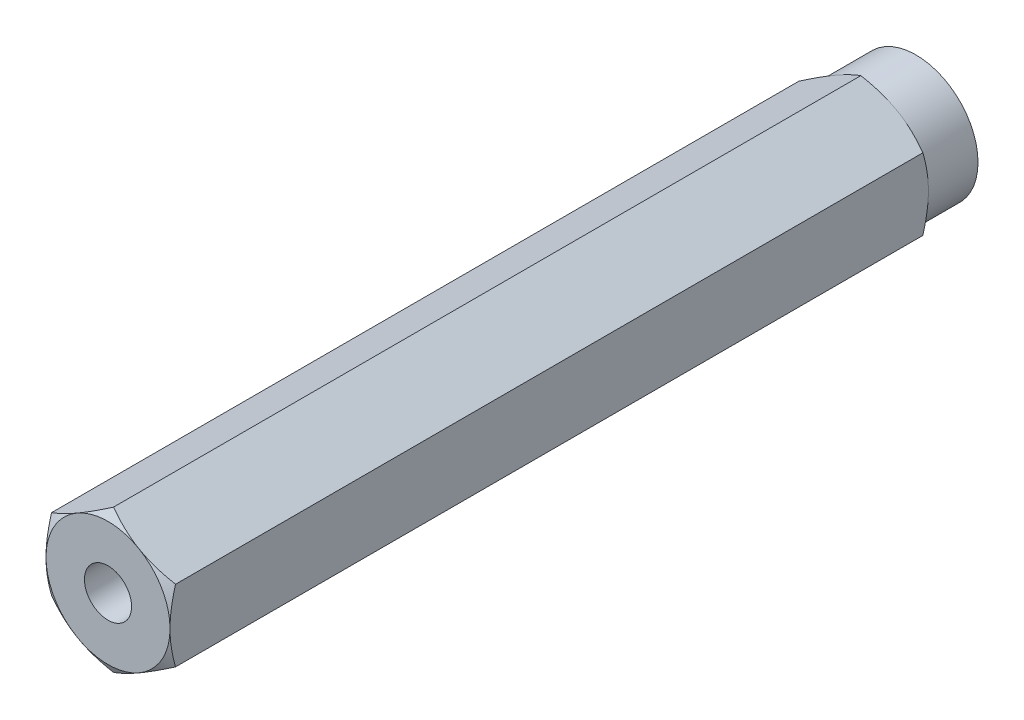
SolidWorks part; units mm, degrees
ref_plane "Front Plane" through (0, 0, 0) normal (0, 0, 1) x (1, 0, 0)
ref_plane "Top Plane" through (0, 0, 0) normal (0, 1, 0) x (1, 0, 0)
ref_plane "Right Plane" through (0, 0, 0) normal (1, 0, 0) x (0, 0, -1)
sketch "Sketch3" plane through (0, 0, 0) normal (1, 0, 0) x (0, 0, -1)
  line L0 (-46.0851, 0) -> (46.0851, 0) construction
  line L1 (0, 6.35) -> (0, -6.35) construction
  line L2 (-46.0851, 2.413) -> (-46.0851, -2.413) construction
  point P2 (33.3851, 0)
  point P3 (-33.3851, 0)
  dimension "Length" = 92.1702
  dimension "Min Thread Length" = 12.7
  dimension "D1" = 12.7
  dimension "Thread Dia" = 4.826
  dimension "Hex" = 12.7
sketch "Sketch1" plane through (0, 0, 0) normal (0, 0, 1) x (1, 0, 0)
  line L1 (0, 7.3323) -> (-6.35, 3.6662)
  line L2 (-6.35, 3.6662) -> (-6.35, -3.6662)
  line L3 (-6.35, -3.6662) -> (0, -7.3323)
  line L4 (0, -7.3323) -> (6.35, -3.6662)
  line L5 (6.35, -3.6662) -> (6.35, 3.6662)
  line L6 (6.35, 3.6662) -> (0, 7.3323)
  circle A0 centre (0, 0) radius 6.35 construction
  circle A1 centre (0, 0) radius 2.413
extrude "Extrude1" add sketch "Sketch1" along normal blind 77.6605
sketch "Sketch11" plane through (0, 0, 0) normal (0, 0, -1) x (-1, 0, 0)
  circle A0 centre (0, 0) radius 2.413 construction
  circle A1 centre (0, 0) radius 2.413
curve "Helix/Spiral1" pitch 0.7937 height 92.964 turns 117.12 parameters "Pitch"=0.7937
sketch "Sketch12" plane through (0, 0, 0) normal (1, 0, 0) x (0, 0, -1)
  line L0 (0.6945, 2.413) -> (0, 2.413)
  line L1 (0.6945, 2.413) -> (0.3969, 1.8974)
  line L2 (0.3969, 1.8974) -> (0.2977, 1.8974)
  line L3 (0.2977, 1.8974) -> (0, 2.413)
  line L4 (0.3473, 1.8974) -> (0.3473, 2.413) construction
  line L5 (0.5457, 2.1552) -> (0.1488, 2.1552) construction
  dimension "D1" = 0.0992
  dimension "D2" = 0.3969
  dimension "D3" = 60
sketch "Sketch6" plane through (0, 0, 0) normal (0, 0, -1) x (-1, 0, 0)
  line L6 (0, 7.3323) -> (-6.35, 3.6662)
  line L7 (-6.35, 3.6662) -> (-6.35, -3.6662)
  line L8 (-6.35, -3.6662) -> (0, -7.3323)
  line L9 (0, -7.3323) -> (6.35, -3.6662)
  line L10 (6.35, -3.6662) -> (6.35, 3.6662)
  line L11 (6.35, 3.6662) -> (0, 7.3323)
  line L12 (0, 7.3323) -> (-6.35, 3.6662)
  line L13 (-6.35, 3.6662) -> (-6.35, -3.6662)
  line L14 (-6.35, -3.6662) -> (0, -7.3323)
  line L15 (0, -7.3323) -> (6.35, -3.6662)
  line L16 (6.35, -3.6662) -> (6.35, 3.6662)
  line L17 (6.35, 3.6662) -> (0, 7.3323)
  dimension "D1" = 0
sketch "Sketch7" plane through (0, 0, 0) normal (0, 0, -1) x (-1, 0, 0)
  circle A2 centre (0, 0) radius 2.4638
  circle A3 centre (0, 0) radius 2.4638
  dimension "D1" = 0.0508
extrude "Extrude3" cut sketch "Sketch7" against normal through all draft 43
sketch "Sketch8" plane through (0, 0, 0) normal (0, 0, -1) x (-1, 0, 0)
  circle A0 centre (0, 0) radius 6.35 construction
  circle A1 centre (0, 0) radius 6.35
extrude "Extrude4" cut sketch "Sketch8" against normal through all draft 60 flip side to cut
sketch3d "3DSketch1"
  point P0 (-1.8275, -4.0911, 77.6605)
ref_plane "Plane1" through (0, 0, 38.8302) normal (0, 0, 1) x (1, 0, 0)
mirror "Mirror1" about plane through (0, 0, 38.8302) normal (0, 0, 1) of "Extrude4"
sketch "Sketch13" plane through (0, 0, 0) normal (0, 0, 1) x (1, 0, 0)
  line L0 (6.35, -3.6662) -> (6.35, 3.6662) construction
  circle A0 centre (0, 0) radius 6.35
  circle A1 centre (0, 0) radius 2.413
  circle A2 centre (0, 0) radius 2.413 construction
extrude "Boss-Extrude1" add sketch "Sketch13" against normal blind 5.08
equation "\"D1@Sketch3\" = \"Min Thread Length@Sketch3\""
equation "\"D3@Helix/Spiral1\" = \"Length@Sketch3\"+\"Pitch@Helix/Spiral1\""
equation "\"D1@Sketch12\" = \"Pitch@Helix/Spiral1\"*.125"
equation "\"D2@Sketch12\" = \"Pitch@Helix/Spiral1\"*.5"
